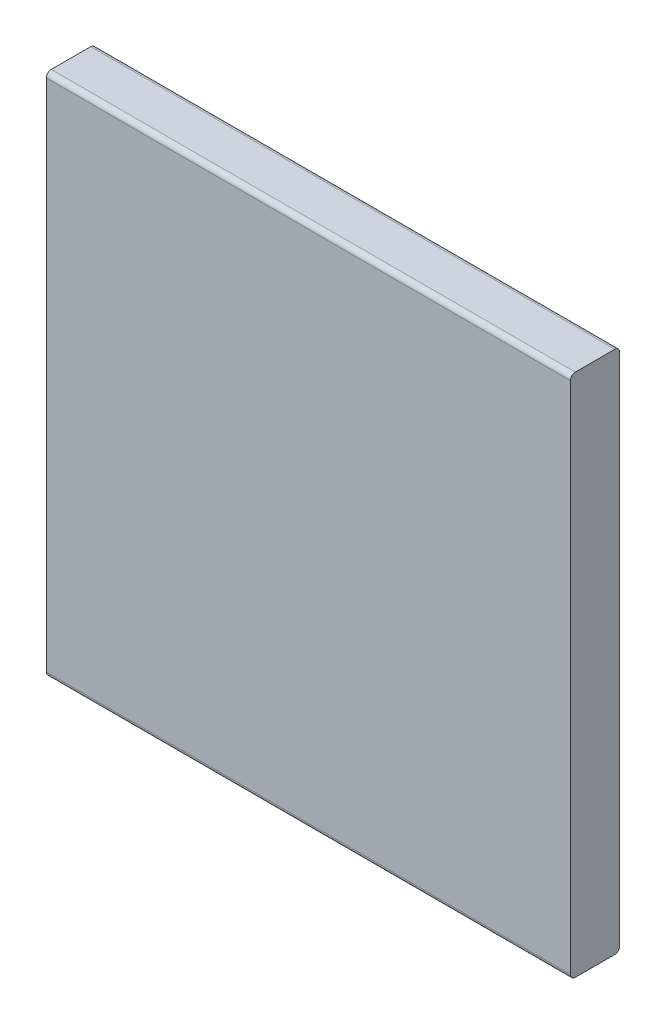
SolidWorks part; units mm, degrees
ref_plane "Front Plane" through (0, 0, 0) normal (0, 0, 1) x (1, 0, 0)
ref_plane "Top Plane" through (0, 0, 0) normal (0, 1, 0) x (1, 0, 0)
ref_plane "Right Plane" through (0, 0, 0) normal (1, 0, 0) x (0, 0, -1)
sketch "Sketch1" plane through (0, 0, 0) normal (0, 0, 1) x (1, 0, 0)
  line L0 (0, -25.4) -> (0, 25.4)
  line L2 (25.4, 0) -> (-25.4, 0)
  line L3 (-25.4, 25.4) -> (25.4, 25.4)
  line L4 (-25.4, 25.4) -> (-25.4, -25.4)
  line L5 (-25.4, -25.4) -> (25.4, -25.4)
  line L6 (25.4, 25.4) -> (25.4, -25.4)
  point P4 (0, 0)
  point P9 (0, 0)
  point P13 (-25.4, -25.4)
  point P14 (25.4, 25.4)
  point P15 (-25.4, 25.4)
  point P16 (25.4, -25.4)
  dimension "Length" = 50.8
  dimension "Width" = 50.8
sketch "Sketch2" plane through (0, 0, 0) normal (1, 0, 0) x (0, 0, -1)
  line L0 (-2.3876, 0) -> (10.3124, 0)
  line L1 (2.3876, 25.4) -> (-2.3876, 25.4)
  line L2 (2.3876, 25.4) -> (2.3876, -25.4)
  line L3 (2.3876, -25.4) -> (-2.3876, -25.4)
  line L4 (-2.3876, 25.4) -> (-2.3876, -25.4)
  point P7 (2.3876, 25.4)
  point P8 (-2.3876, 25.4)
  dimension "Thickness" = 4.7752
  dimension "Mounting Fastener Thread Length" = 12.7
sketch "Sketch3" plane through (0, 0, 0) normal (0, 0, 1) x (1, 0, 0)
  line L0 (-25.4, -25.4) -> (25.4, -25.4) construction
  line L1 (25.4, 25.4) -> (25.4, -25.4) construction
  line L2 (-25.4, 25.4) -> (-25.4, -25.4) construction
  line L3 (-25.4, 25.4) -> (25.4, 25.4) construction
  line L4 (-25.4, -25.4) -> (25.4, -25.4)
  line L5 (25.4, 25.4) -> (25.4, -25.4)
  line L6 (-25.4, 25.4) -> (-25.4, -25.4)
  line L7 (-25.4, 25.4) -> (25.4, 25.4)
extrude "Boss-Extrude1" add sketch "Sketch3" against normal up to vertex (2.3876 mm away) and the other way up to vertex (2.3876 mm away) up to point (0, 25.4, -2.3876) other way up to point (0, 25.4, 2.3876)
fillet "Fillet1" radius 0.4775 4 edges at (0, -25.4, 2.3876) (0, -25.4, -2.3876) (0, 25.4, 2.3876) (0, 25.4, -2.3876)
equation "\"D1@Fillet1\"=\"Thickness@Sketch2\"*.1"
